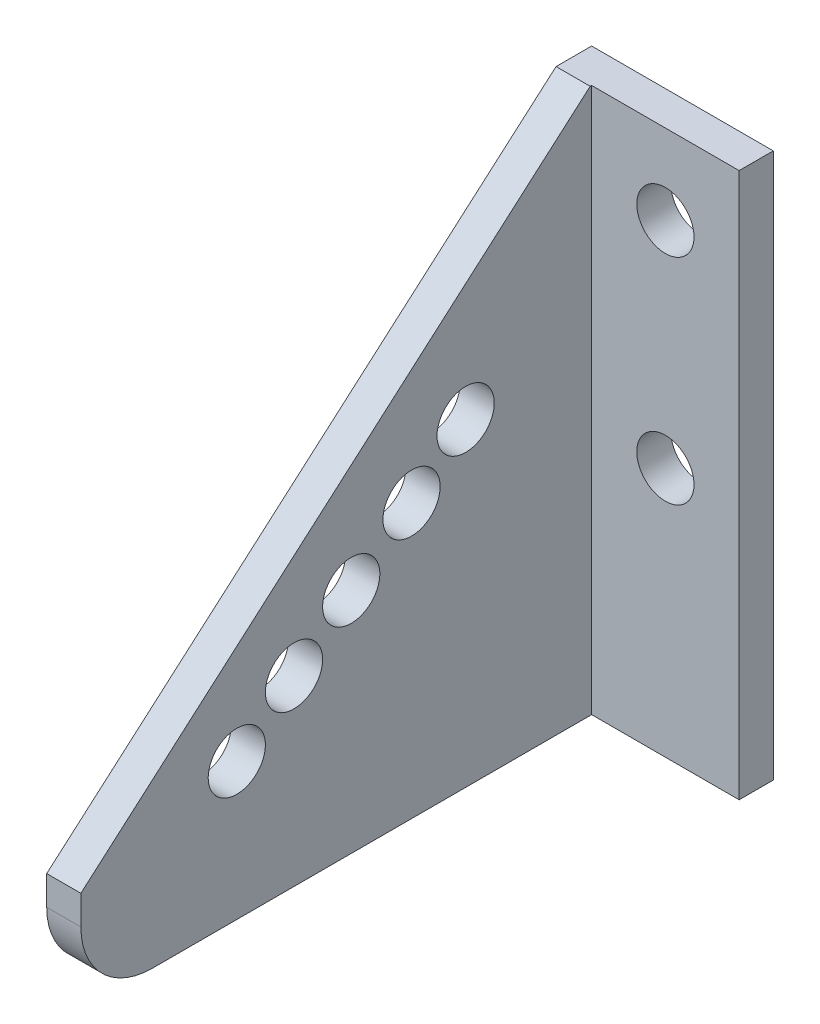
SolidWorks part; units mm, degrees
material "6061-T6 (SS)"
ref_plane "Front Plane" through (0, 0, 0) normal (0, 0, 1) x (1, 0, 0)
ref_plane "Top Plane" through (0, 0, 0) normal (0, 1, 0) x (1, 0, 0)
ref_plane "Right Plane" through (0, 0, 0) normal (1, 0, 0) x (0, 0, -1)
sketch "Sketch1" plane through (0, 0, 0) normal (0, 1, 0) x (1, 0, 0)
  line L0 (0, -76.2) -> (0, 0)
  line L1 (0, 0) -> (25.4, 0)
  line L2 (4.7752, -76.2) -> (4.7752, -4.7752)
  line L3 (4.7752, -4.7752) -> (25.4, -4.7752)
  line L4 (25.4, 0) -> (25.4, -4.7752)
  line L5 (4.7752, -76.2) -> (0, -76.2)
  dimension "D1" = 25.4
  dimension "D2" = 76.2
  dimension "D3" = 4.7752
extrude "Boss-Extrude1" add sketch "Sketch1" along normal blind 76.2
sketch "Sketch2" plane through (0, 0, 0) normal (-1, 0, 0) x (0, 0, 1)
  line L0 (4.9778, 76.2) -> (76.2, 14.0825)
  line L1 (76.2, 76.2) -> (76.2, 0) construction
  line L3 (4.9778, 76.2) -> (76.2, 76.2)
  line L4 (33.171, 36.1416) -> (39.2629, 36.1416) construction
  line L5 (22.396, 44.5634) -> (22.396, 38.2134) construction
  line L6 (22.396, 38.2134) -> (30.396, 38.2134) construction
  line L7 (30.396, 38.2134) -> (30.396, 31.8634) construction
  line L8 (30.396, 31.8634) -> (38.396, 31.8634) construction
  line L9 (49.171, 23.4416) -> (49.171, 17.0916) construction
  line L10 (38.396, 25.5134) -> (46.396, 25.5134) construction
  line L11 (46.396, 25.5134) -> (46.396, 19.1634) construction
  line L12 (46.396, 19.1634) -> (54.396, 19.1634) construction
  line L13 (0, 76.2) -> (76.2, 76.2) construction
  line L14 (76.2, 14.0825) -> (76.2, 76.2)
  line L15 (54.396, 19.1634) -> (22.396, 44.5634) construction
  line L16 (22.396, 44.5634) -> (-1.0497, 63.1735) construction
  line L17 (85.333, 14.0825) -> (76.2, 10)
  line L19 (66.2, 0) -> (61.0329, 0)
  line L20 (0, 0) -> (76.2, 0) construction
  line L21 (61.0329, 0) -> (61.0329, -6.2558)
  line L22 (61.0329, -6.2558) -> (85.333, -6.2558)
  line L23 (85.333, -6.2558) -> (85.333, 14.0825)
  circle A0 centre (22.396, 44.5634) radius 4
  circle A5 centre (29.9568, 38.2134) radius 4
  circle A6 centre (38.396, 31.8634) radius 4
  circle A7 centre (46.396, 25.5134) radius 4
  circle A8 centre (54.396, 19.1634) radius 4
  arc A9 (76.2, 10) -> (66.2, 0) centre (66.2, 10) cw
  point P36 (76.2, 0)
  dimension "D1" = 8
  dimension "D3" = 8
  dimension "D4" = 10
  dimension "D2" = 6.35
extrude "Cut-Extrude1" cut sketch "Sketch2" against normal blind 76.2
sketch "Sketch3" plane through (0, 0, 4.7752) normal (0, 0, 1) x (1, 0, 0)
  line L0 (15.0876, 76.2) -> (15.0876, 0) construction
  line L1 (4.7752, 76.2) -> (25.4, 76.2) construction
  line L2 (4.7752, 0) -> (25.4, 0) construction
  circle A0 centre (15.0876, 65) radius 4
  circle A1 centre (15.0876, 35) radius 4
  dimension "D1" = 8
  dimension "D2" = 35
  dimension "D3" = 30
extrude "Cut-Extrude2" cut sketch "Sketch3" against normal blind 76.2
